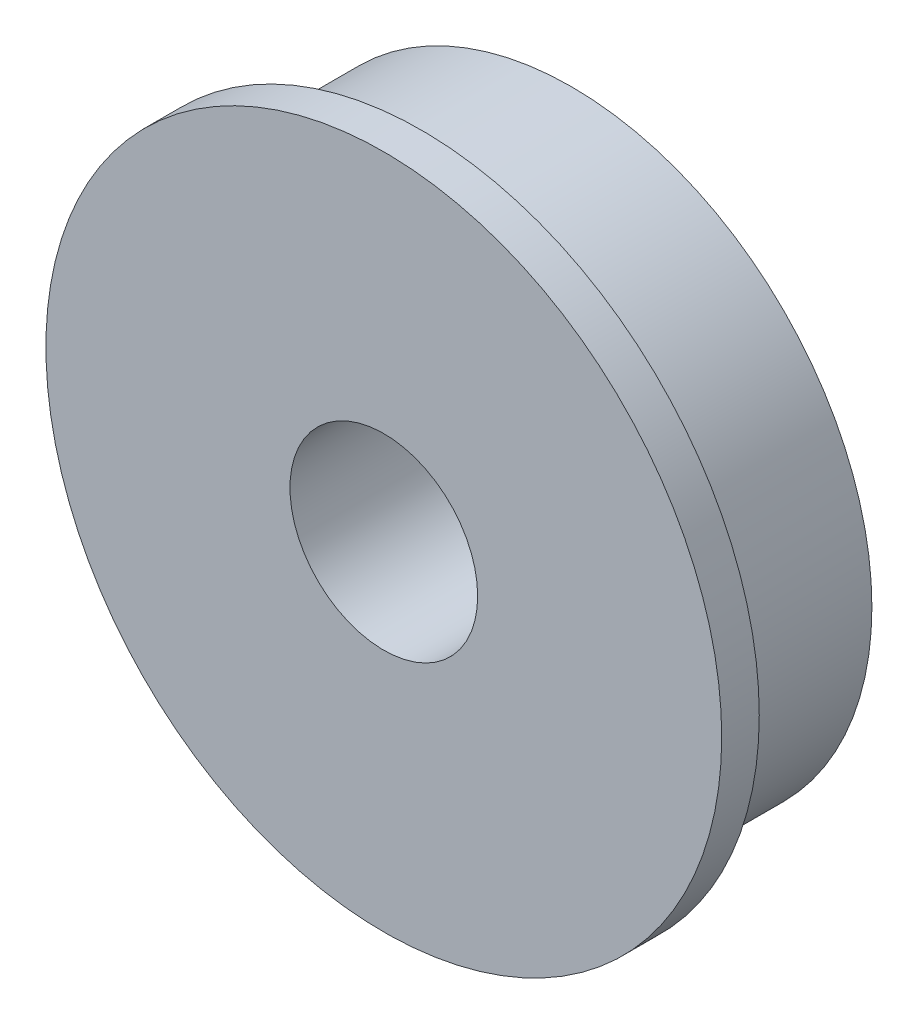
SolidWorks part; units mm, degrees
ref_plane "前视基准面" through (0, 0, 0) normal (0, 0, 1) x (1, 0, 0)
ref_plane "上视基准面" through (0, 0, 0) normal (0, 1, 0) x (1, 0, 0)
ref_plane "右视基准面" through (0, 0, 0) normal (1, 0, 0) x (0, 0, -1)
sketch "草图1" plane through (0, 0, 0) normal (0, 0, 1) x (1, 0, 0)
  circle A0 centre (0, 0) radius 2.5
  circle A1 centre (0, 0) radius 8
extrude "凸台-拉伸1" add sketch "草图1" along normal blind 4
sketch "草图2" plane through (0, 0, 4) normal (0, 0, 1) x (1, 0, 0)
  circle A0 centre (0, 0) radius 9
  circle A1 centre (0, 0) radius 2.5 construction
  circle A2 centre (0, 0) radius 2.5
extrude "凸台-拉伸2" add sketch "草图2" along normal blind 1
